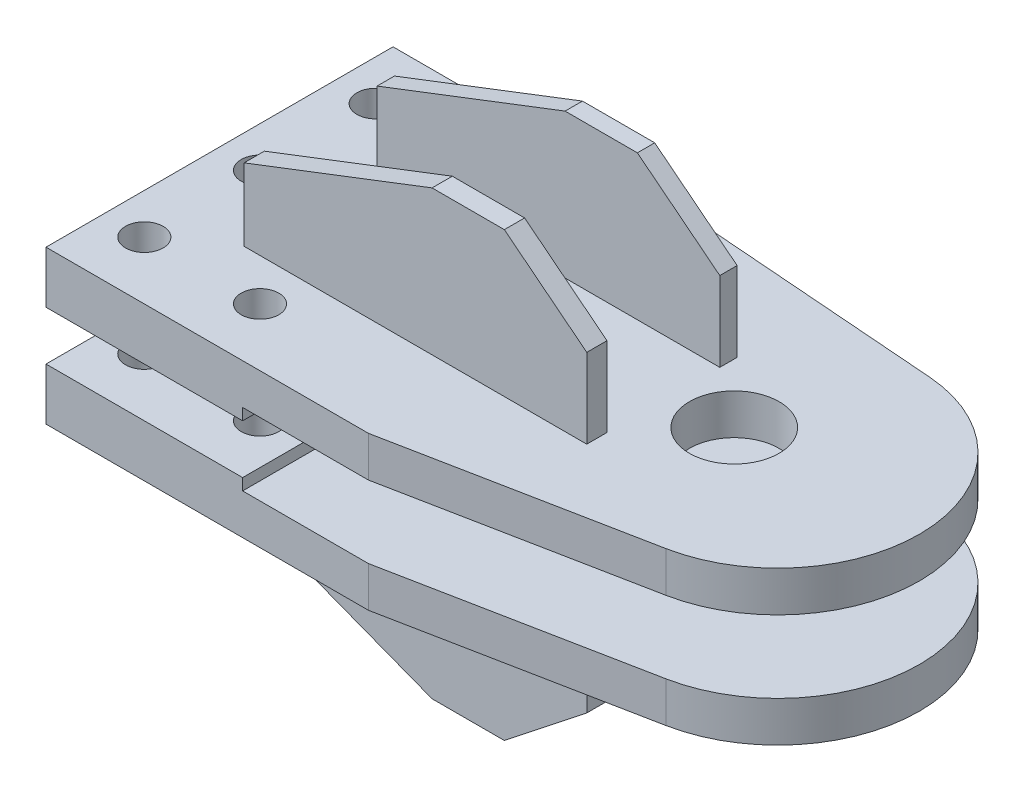
SolidWorks part; units mm, degrees
ref_plane "前视基准面" through (0, 0, 0) normal (0, 0, 1) x (1, 0, 0)
ref_plane "上视基准面" through (0, 0, 0) normal (0, 1, 0) x (1, 0, 0)
ref_plane "右视基准面" through (0, 0, 0) normal (1, 0, 0) x (0, 0, -1)
sketch "草图1" plane through (0, 0, 0) normal (0, 1, 0) x (1, 0, 0)
  line L0 (-1000, 0) -> (49000, 0) construction
  line L1 (0, 120) -> (0, -120)
  line L2 (0, 120) -> (223, 120)
  line L3 (223, 120) -> (383.4807, 107.7141)
  line L4 (0, -120) -> (223, -120)
  line L5 (223, -120) -> (394.9287, -86.1546)
  line L6 (-654, 10) -> (49346, 10) construction
  circle A0 centre (346, 10) radius 31
  arc A1 (383.4807, 107.7141) -> (394.9287, -86.1546) centre (376, 10) cw
  circle A2 centre (28, 80) radius 13
  circle A3 centre (28, 0) radius 13
  circle A4 centre (28, -80) radius 13
  circle A5 centre (108, 80) radius 13
  circle A6 centre (108, 0) radius 13
  circle A7 centre (108, -80) radius 13
  dimension "D2" = 62
  dimension "D3" = 98
  dimension "D11" = 26
  dimension "D1" = 346
  dimension "D4" = 240
  dimension "D5" = 223
  dimension "D6" = 10
  dimension "D7" = 28
  dimension "D8" = 80
  dimension "D9" = 80
  dimension "D10" = 80
  dimension "D12" = 30
extrude "凸台-拉伸1" add sketch "草图1" along normal blind 28
sketch "草图2" plane through (0, 28, 0) normal (0, 1, 0) x (1, 0, 0)
  line L0 (-1000, 0) -> (49000, 0) construction
  line L1 (68, 53) -> (305, 53)
  line L2 (68, 53) -> (68, 41)
  line L3 (68, 41) -> (305, 41)
  line L4 (305, 53) -> (305, 41)
  line L5 (68, -37) -> (305, -37)
  line L6 (68, -37) -> (68, -51)
  line L7 (68, -51) -> (305, -51)
  line L8 (305, -37) -> (305, -51)
  line L9 (0, 120) -> (0, -120) construction
  line L10 (223, 120) -> (0, 120) construction
  line L11 (0, -120) -> (223, -120) construction
  dimension "D1" = 78
  dimension "D2" = 12
  dimension "D3" = 68
  dimension "D4" = 237
  dimension "D5" = 67
  dimension "D6" = 69
extrude "凸台-拉伸2" add sketch "草图2" along normal blind 100
sketch "草图3" plane through (0, 0, -53) normal (0, 0, -1) x (1, 0, 0)
  line L0 (305, -128) -> (305, -83)
  line L1 (305, -128) -> (305, -28) construction
  line L2 (305, -83) -> (248, -128)
  line L3 (305, -128) -> (68, -128) construction
  line L4 (248, -128) -> (305, -128)
  line L5 (68, -128) -> (68, -78)
  line L6 (68, -128) -> (68, -28) construction
  line L7 (68, -78) -> (198, -128)
  line L8 (198, -128) -> (68, -128)
  line L9 (305, -28) -> (68, -28) construction
  line L10 (383.4807, -28) -> (223, -28) construction
  dimension "D1" = 50
  dimension "D2" = 130
  dimension "D3" = 57
  dimension "D4" = 55
extrude "切除-拉伸1" cut sketch "草图3" against normal through all
sketch "草图4" plane through (0, 0, 0) normal (0, -1, 0) x (-1, 0, 0)
  line L0 (-68, -994.8965) -> (-68, 49005.1035) construction
  line L1 (-223, 120) -> (0, 120) construction
  line L3 (0, -120) -> (-136, -120)
  line L4 (0, -120) -> (0, 120)
  line L5 (0, 120) -> (-136, 120)
  line L6 (-136, -120) -> (-136, 120)
  circle A0 centre (-28, -80) radius 13 construction
  circle A1 centre (-108, -80) radius 13 construction
  circle A2 centre (-28, -80) radius 13
  circle A3 centre (-108, -80) radius 13
  circle A4 centre (-28, 0) radius 13
  circle A5 centre (-108, 0) radius 13
  circle A6 centre (-28, 80) radius 13
  circle A7 centre (-108, 80) radius 13
  circle A8 centre (-28, 0) radius 13 construction
  circle A9 centre (-108, 0) radius 13 construction
  circle A10 centre (-28, 80) radius 13 construction
  circle A11 centre (-108, 80) radius 13 construction
extrude "凸台-拉伸3" add sketch "草图4" along normal blind 8
ref_plane "基准面1" through (0, -25, 0) normal (0, 1, 0) x (1, 0, 0)
mirror "镜向1" about plane through (0, -25, 0) normal (0, 1, 0) of bodies 110 108
